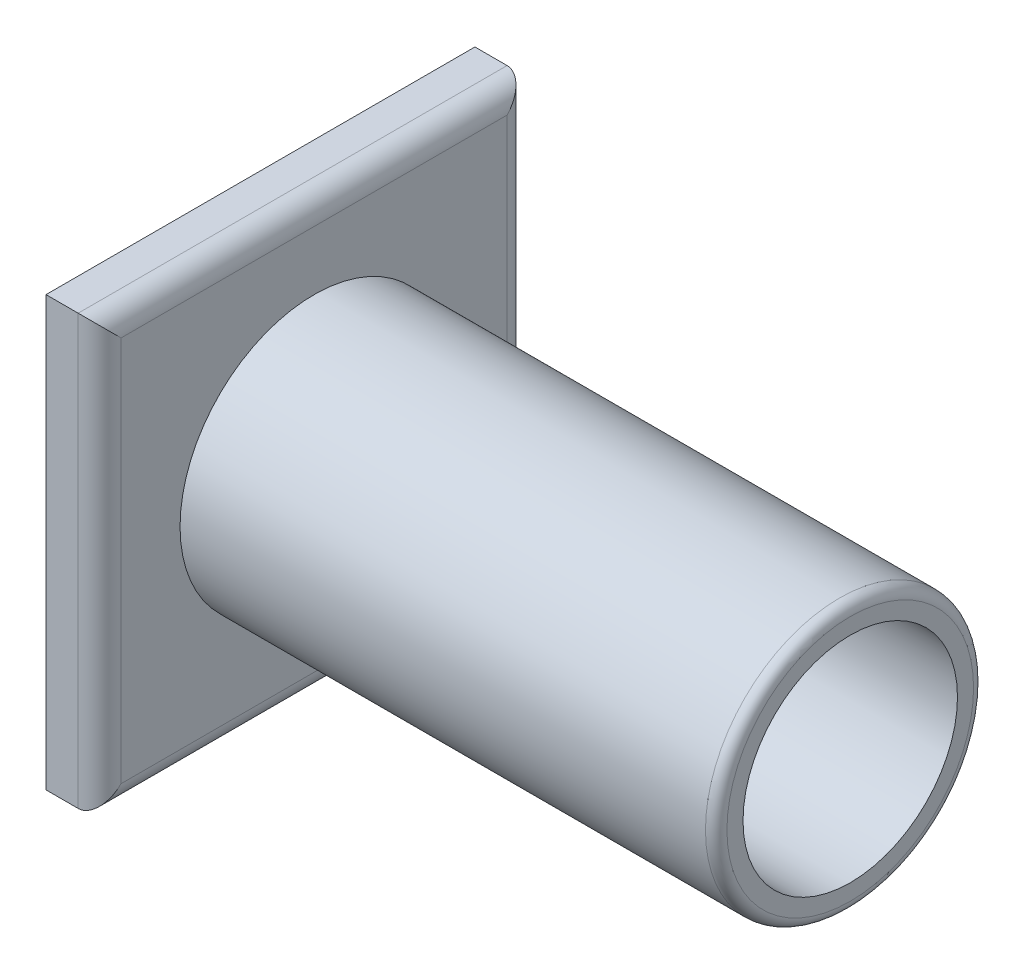
SolidWorks part; units mm, degrees
ref_plane "Front Plane" through (0, 0, 0) normal (0, 0, 1) x (1, 0, 0)
ref_plane "Top Plane" through (0, 0, 0) normal (0, 1, 0) x (1, 0, 0)
ref_plane "Right Plane" through (0, 0, 0) normal (1, 0, 0) x (0, 0, -1)
sketch "Sketch3" plane through (0, 0, 0) normal (1, 0, 0) x (0, 0, -1)
  line L1 (-400, -400) -> (400, -400)
  line L2 (-400, -400) -> (-400, 400)
  line L3 (-400, 400) -> (400, 400)
  line L4 (400, -400) -> (400, 400)
  line L5 (-400, -400) -> (400, 400) construction
  line L6 (-400, 400) -> (400, -400) construction
  point P0 (0, 0)
  dimension "D1" = 800
  dimension "D2" = 800
extrude "Boss-Extrude1" add sketch "Sketch3" along normal blind 100
sketch "Sketch4" plane through (100, 0, 0) normal (1, 0, 0) x (0, 0, -1)
  circle A0 centre (0, 0) radius 200
  circle A1 centre (0, 0) radius 250
  dimension "D1" = 400
  dimension "D2" = 500
extrude "Boss-Extrude2" add sketch "Sketch4" along normal blind 1000
fillet "Fillet3" radius 40 4 edges at (100, 0, 400) (100, -400, 0) (100, 400, 0) (100, 0, -400)
fillet "Fillet4" radius 20 1 edges at (1100, 0, -250)
